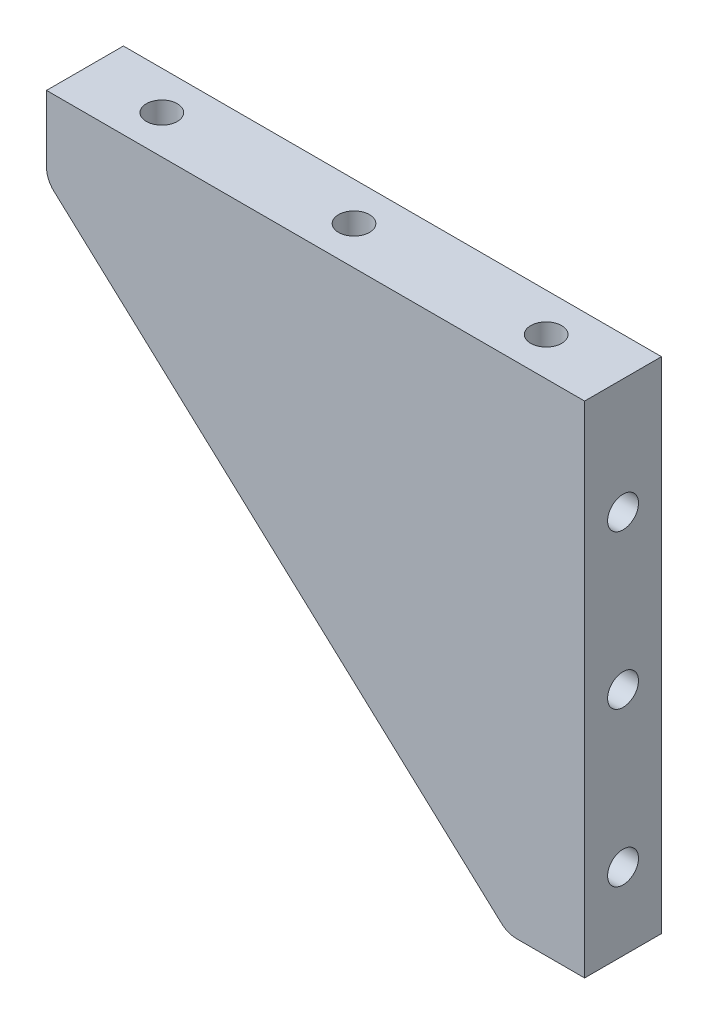
SolidWorks part; units mm, degrees
ref_plane "Front Plane" through (0, 0, 0) normal (0, 0, 1) x (1, 0, 0)
ref_plane "Top Plane" through (0, 0, 0) normal (0, 1, 0) x (1, 0, 0)
ref_plane "Right Plane" through (0, 0, 0) normal (1, 0, 0) x (0, 0, -1)
sketch "Sketch1" plane through (0, 0, 0) normal (0, 0, 1) x (1, 0, 0)
  line L0 (0, 0) -> (-88.9, 0)
  line L1 (-88.9, 0) -> (-88.9, -12.7)
  line L2 (-88.9, -12.7) -> (-12.7, -82.55)
  line L3 (-12.7, -82.55) -> (0, -82.55)
  line L4 (0, -82.55) -> (0, 0)
  dimension "D1" = 12.7
  dimension "D2" = 82.55
  dimension "D3" = 88.9
extrude "Boss-Extrude1" add sketch "Sketch1" along normal mid plane 12.7
hole_wizard "Tap Drill for 1/4-20 Tap1" positions "Sketch2" profile "Sketch3" hole size "1/4-20" standard "ANSI Inch"
sketch "Sketch2" plane through (0, 0, 0) normal (0, 1, 0) x (1, 0, 0)
  line L1 (-88.9, -6.35) -> (-88.9, 6.35) construction
  point P0 (-76.2, 0)
  dimension "D1" = 12.7
sketch "Sketch3" plane through (-76.2, 0, 0) normal (1, 0, 0) x (0, 0, 1)
  line L0 (0, 0) -> (0, 14.2338)
  line L1 (0, 14.2338) -> (2.5527, 12.7)
  line L2 (2.5527, 12.7) -> (2.5527, 0)
  line L5 (2.5527, 0) -> (0, 0)
  line L10 (0, 14.2338) -> (-2.5527, 12.7) construction
  line L11 (0, -6.35) -> (0, 107.95) construction
  dimension "Hole Dia." = 5.1054
  dimension "Hole Depth" = 12.7
  dimension "Drill Angle" = 118
pattern_linear "LPattern1" count 3 spacing 31.75 along (1, 0, 0) of "Tap Drill for 1/4-20 Tap1"
hole_wizard "Tap Drill for 1/4-20 Tap2" positions "Sketch4" profile "Sketch5" hole size "1/4-20" standard "ANSI Inch"
sketch "Sketch4" plane through (0, 0, 0) normal (1, 0, 0) x (0, 0, -1)
  line L1 (-6.35, -82.55) -> (6.35, -82.55) construction
  point P2 (0, -69.85)
  dimension "D1" = 12.7
sketch "Sketch5" plane through (0, -69.85, 0) normal (0, 1, 0) x (0, 0, -1)
  line L0 (0, 0) -> (0, 14.2338)
  line L1 (0, 14.2338) -> (2.5527, 12.7)
  line L2 (2.5527, 12.7) -> (2.5527, 0)
  line L5 (2.5527, 0) -> (0, 0)
  line L10 (0, 14.2338) -> (-2.5527, 12.7) construction
  line L11 (0, -6.35) -> (0, 107.95) construction
  dimension "Hole Dia." = 5.1054
  dimension "Hole Depth" = 12.7
  dimension "Drill Angle" = 118
pattern_linear "LPattern2" count 3 spacing 25.4 along (0, 1, 0) of "Tap Drill for 1/4-20 Tap2"
fillet "Fillet1" radius 3.81 2 edges at (-88.9, -12.7, 0) (-12.7, -82.55, 0)
